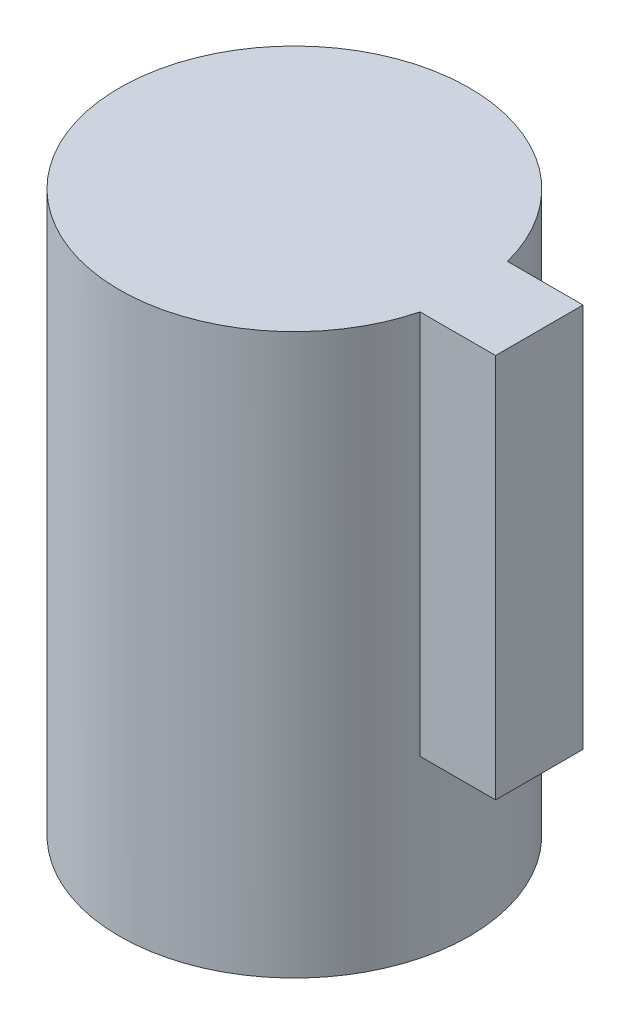
SolidWorks part; units mm, degrees
ref_plane "Front Plane" through (0, 0, 0) normal (0, 0, 1) x (1, 0, 0)
ref_plane "Top Plane" through (0, 0, 0) normal (0, 1, 0) x (1, 0, 0)
ref_plane "Right Plane" through (0, 0, 0) normal (1, 0, 0) x (0, 0, -1)
sketch "Sketch1" plane through (0, 0, 0) normal (0, 1, 0) x (1, 0, 0)
  circle A0 centre (0, 0) radius 5
  dimension "D1" = 10
extrude "Boss-Extrude1" add sketch "Sketch1" along normal mid plane 16
sketch "Sketch2" plane through (0, 8, 0) normal (0, 1, 0) x (1, 0, 0)
  line L1 (0, 1.25) -> (7, 1.25)
  line L2 (0, 1.25) -> (0, -1.25)
  line L3 (0, -1.25) -> (7, -1.25)
  line L4 (7, 1.25) -> (7, -1.25)
  dimension "D1" = 7
  dimension "D2" = 2.5
extrude "Boss-Extrude2" add sketch "Sketch2" against normal blind 11
